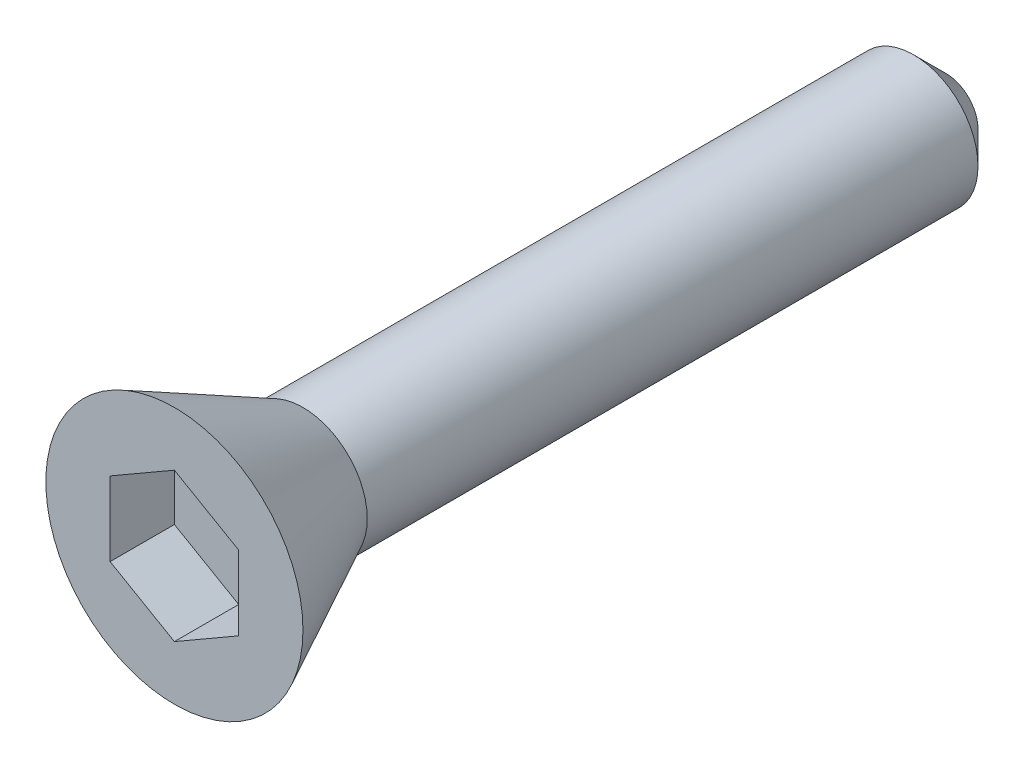
SolidWorks part; units mm, degrees
ref_plane "Front Plane" through (0, 0, 0) normal (0, 0, 1) x (1, 0, 0)
ref_plane "Top Plane" through (0, 0, 0) normal (0, 1, 0) x (1, 0, 0)
ref_plane "Right Plane" through (0, 0, 0) normal (1, 0, 0) x (0, 0, -1)
sketch "Sketch1" plane through (0, 0, 0) normal (1, 0, 0) x (0, 0, -1)
  line L0 (-58.5147, 0) -> (2867.2225, 0) construction
  line L1 (0, 0) -> (0, 2)
  line L2 (0, 2) -> (2, 1)
  line L3 (2, 1) -> (12, 1)
  line L4 (12, 1) -> (12, 0)
  line L5 (12, 0) -> (0, 0)
  dimension "D1" = 2
  dimension "D2" = 4
  dimension "D3" = 10
  dimension "D4" = 2
revolve "Body" add sketch "Sketch1" angle 360 about L0
sketch "Sketch2" plane through (0, 0, 0) normal (0, 0, 1) x (1, 0, 0)
  line L1 (0, 1.1547) -> (-1, 0.5774)
  line L2 (-1, 0.5774) -> (-1, -0.5774)
  line L3 (-1, -0.5774) -> (0, -1.1547)
  line L4 (0, -1.1547) -> (1, -0.5774)
  line L5 (1, -0.5774) -> (1, 0.5774)
  line L6 (1, 0.5774) -> (0, 1.1547)
  circle A0 centre (0, 0) radius 1 construction
  dimension "D1" = 2
extrude "Footprint" cut sketch "Sketch2" against normal blind 1
chamfer "Chamfer1" distance 0.5 angle 45 1 edges at (1, 0, -12)
